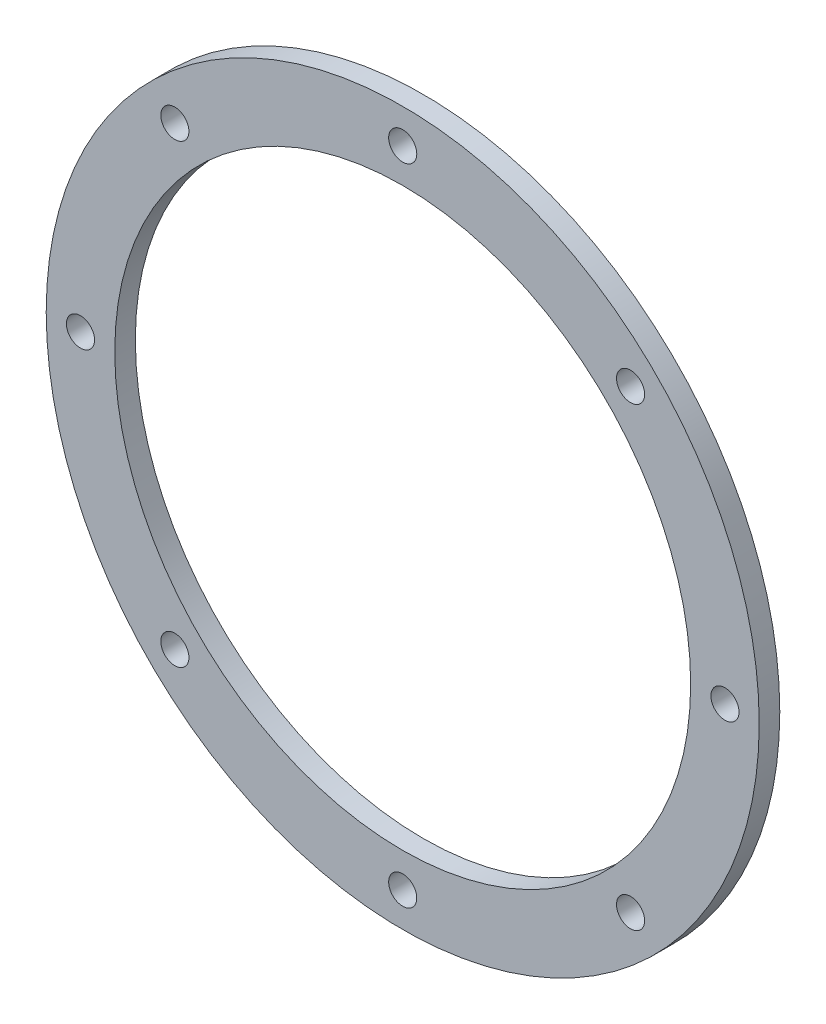
SolidWorks part; units mm, degrees
ref_plane "Front Plane" through (0, 0, 0) normal (0, 0, 1) x (1, 0, 0)
ref_plane "Top Plane" through (0, 0, 0) normal (0, 1, 0) x (1, 0, 0)
ref_plane "Right Plane" through (0, 0, 0) normal (1, 0, 0) x (0, 0, -1)
sketch "Sketch1" plane through (0, 0, 0) normal (0, 0, 1) x (1, 0, 0)
  circle A0 centre (0, 0) radius 52
  circle A1 centre (0, 0) radius 42
  dimension "D1" = 104
  dimension "D2" = 10
extrude "Boss-Extrude1" add sketch "Sketch1" along normal blind 3
sketch "Sketch2" plane through (0, 0, 3) normal (0, 0, 1) x (1, 0, 0)
  line L0 (0, 52) -> (0, 47) construction
  line L1 (0, 47) -> (0, 0) construction
  circle A0 centre (0, 47) radius 2.05
  circle A1 centre (0, 0) radius 52 construction
  dimension "D2" = 4.1
  dimension "D1" = 5
extrude "Cut-Extrude1" cut sketch "Sketch2" against normal blind 3
pattern_circular "CirPattern1" count 8 over 360 about axis through (0, 0, 0) along (0, 0, 1) of "Cut-Extrude1"
